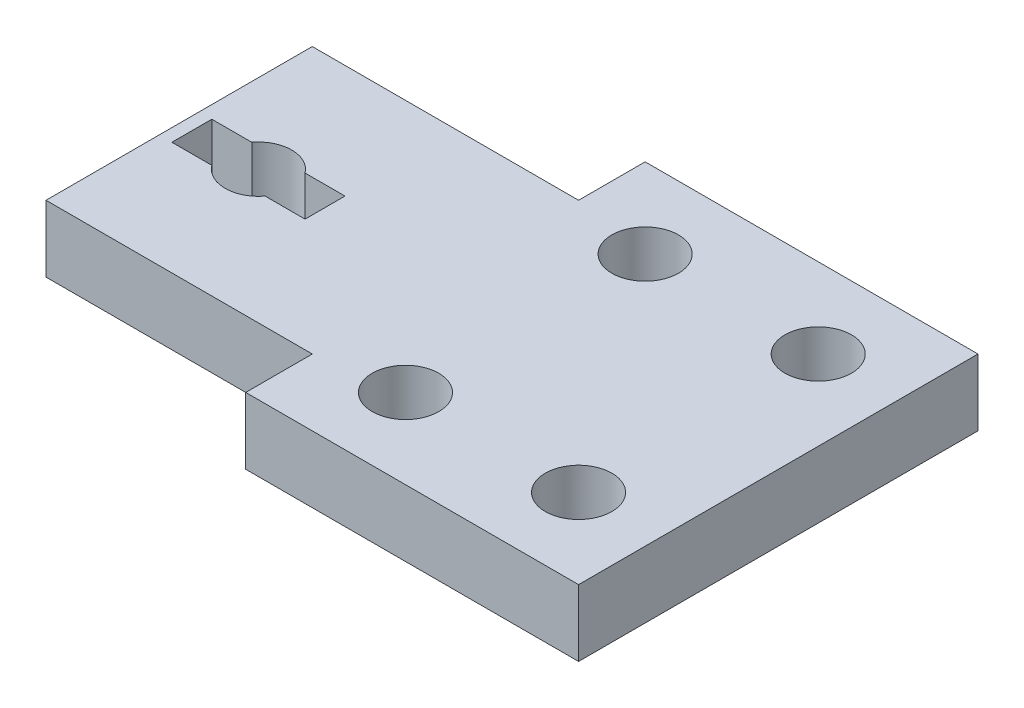
SolidWorks part; units mm, degrees
ref_plane "Front Plane" through (0, 0, 0) normal (0, 0, 1) x (1, 0, 0)
ref_plane "Top Plane" through (0, 0, 0) normal (0, 1, 0) x (1, 0, 0)
ref_plane "Right Plane" through (0, 0, 0) normal (1, 0, 0) x (0, 0, -1)
sketch "Sketch1" plane through (0, 0, 0) normal (0, 0, 1) x (1, 0, 0)
  line L0 (0, 0) -> (25, 0)
  line L1 (25, 0) -> (25, 5)
  line L2 (25, 5) -> (0, 5)
  line L3 (0, 5) -> (0, 0)
  dimension "D1" = 5
  dimension "D2" = 25
extrude "Boss-Extrude2" add sketch "Sketch1" along normal blind 30
sketch "Sketch2" plane through (0, 5, 0) normal (0, 1, 0) x (1, 0, 0)
  line L0 (0, -30) -> (0, 0) construction
  line L1 (25, -30) -> (25, 0) construction
  line L2 (25, -30) -> (0, -30) construction
  line L3 (25, 0) -> (0, 0) construction
  circle A0 centre (6, -6) radius 2.5
  circle A1 centre (19, -6) radius 2.5
  circle A2 centre (19, -24) radius 2.5
  circle A3 centre (6, -24) radius 2.5
  dimension "D4" = 5
  dimension "D1" = 6
  dimension "D2" = 6
  dimension "D3" = 6
  dimension "D5" = 6
extrude "Cut-Extrude1" cut sketch "Sketch2" against normal through all both and the other way through all
sketch "Sketch5" plane through (0, 0, 0) normal (-1, 0, 0) x (0, 0, 1)
  line L0 (30, 5) -> (0, 5) construction
  line L1 (5, 5) -> (25, 5)
  line L2 (5, 5) -> (5, 0)
  line L3 (5, 0) -> (25, 0)
  line L4 (25, 5) -> (25, 0)
  line L5 (30, 0) -> (0, 0) construction
  line L6 (0, 5) -> (0, 0) construction
  line L7 (30, 5) -> (30, 0) construction
  dimension "D1" = 5
  dimension "D2" = 5
extrude "Boss-Extrude3" add sketch "Sketch5" along normal blind 20
sketch "Sketch6" plane through (0, 5, 0) normal (0, 1, 0) x (1, 0, 0)
  line L0 (-12.0446, -13.5) -> (-9.0446, -13.5)
  line L1 (-9.0446, -13.5) -> (-9.0446, -16.5)
  line L2 (-9.0446, -16.5) -> (-12.0446, -16.5)
  line L3 (-16.0446, -16.5) -> (-19.0446, -16.5)
  line L4 (-19.0446, -16.5) -> (-19.0446, -13.5)
  line L5 (-19.0446, -13.5) -> (-16.0446, -13.5)
  arc A0 (-12.0446, -13.5) -> (-16.0446, -13.5) centre (-14.0446, -15) ccw
  arc A1 (-16.0446, -16.5) -> (-12.0446, -16.5) centre (-14.0446, -15) ccw
  dimension "D1" = 2.5
  dimension "D2" = 3
  dimension "D3" = 3
  dimension "D5" = 3
  dimension "D6" = 3
extrude "Cut-Extrude3" cut sketch "Sketch6" against normal through all
